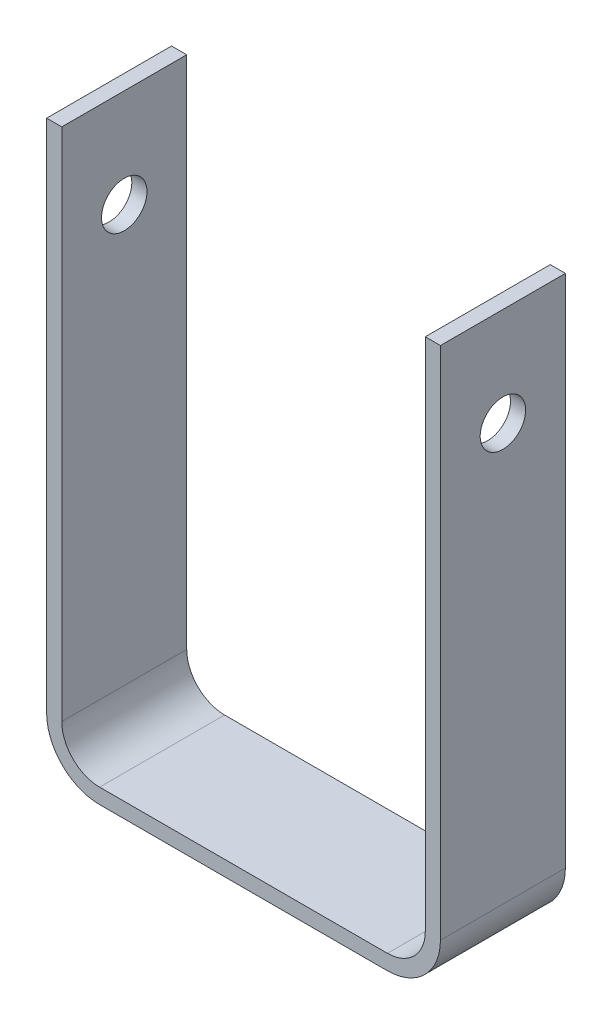
SolidWorks part; units mm, degrees
ref_plane "Спереди" through (0, 0, 0) normal (0, 0, 1) x (1, 0, 0)
ref_plane "Сверху" through (0, 0, 0) normal (0, 1, 0) x (1, 0, 0)
ref_plane "Справа" through (0, 0, 0) normal (1, 0, 0) x (0, 0, -1)
sketch "Эскиз1" plane through (0, 0, 0) normal (0, 0, 1) x (1, 0, 0)
  line L0 (0, 0) -> (38, 0)
  line L1 (52, 14) -> (52, 150)
  line L2 (0, 4) -> (38, 4)
  line L3 (48, 14) -> (48, 150)
  line L4 (48, 150) -> (52, 150)
  line L5 (0, 0) -> (0, 190.2591) construction
  line L6 (-48, 150) -> (-52, 150)
  line L7 (-48, 14) -> (-48, 150)
  line L8 (0, 4) -> (-38, 4)
  line L9 (-52, 14) -> (-52, 150)
  line L10 (0, 0) -> (-38, 0)
  arc A0 (38, 0) -> (52, 14) centre (38, 14) ccw
  arc A1 (38, 4) -> (48, 14) centre (38, 14) ccw
  arc A2 (-38, 4) -> (-48, 14) centre (-38, 14) cw
  arc A3 (-38, 0) -> (-52, 14) centre (-38, 14) cw
  point P6 (52, 0)
  dimension "D3" = 14
  dimension "D1" = 52
  dimension "D2" = 150
  dimension "D4" = 4
extrude "Бобышка-Вытянуть1" add sketch "Эскиз1" along normal blind 33
sketch "Эскиз2" plane through (52, 0, 0) normal (1, 0, 0) x (0, 0, -1)
  line L0 (-33, 150) -> (0, 150) construction
  circle A0 centre (-16.5, 124) radius 6
  point P5 (-16.5, 150)
  dimension "D1" = 20
  dimension "D2" = 12
extrude "Вырез-Вытянуть1" cut sketch "Эскиз2" against normal through all both and the other way through all
